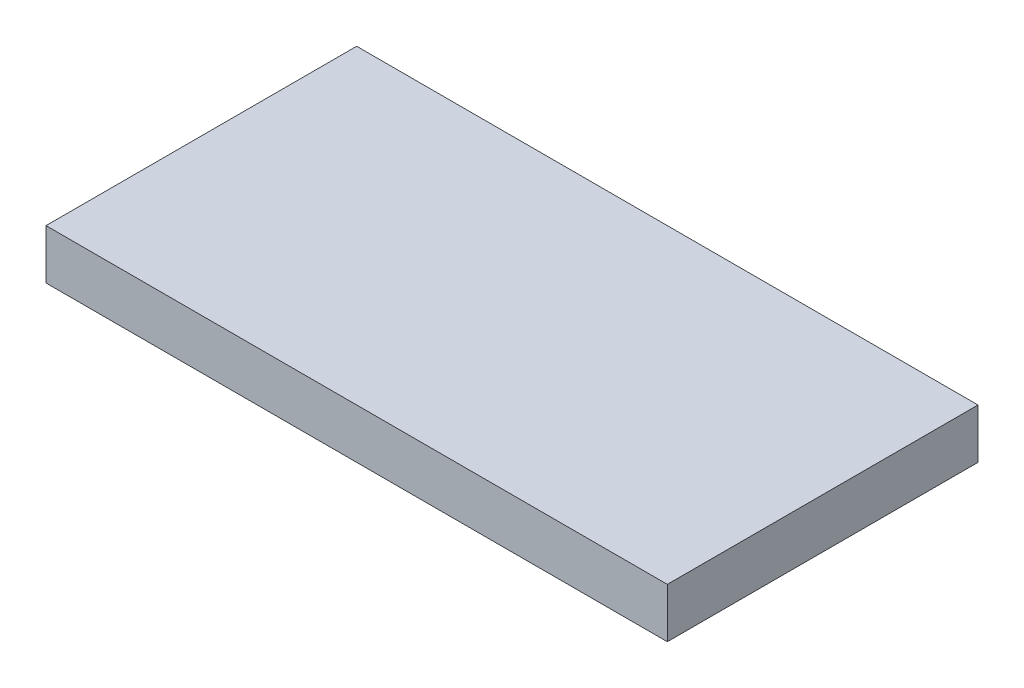
SolidWorks part; units mm, degrees
ref_plane "Front Plane" through (0, 0, 0) normal (0, 0, 1) x (1, 0, 0)
ref_plane "Top Plane" through (0, 0, 0) normal (0, 1, 0) x (1, 0, 0)
ref_plane "Right Plane" through (0, 0, 0) normal (1, 0, 0) x (0, 0, -1)
sketch "Sketch1" plane through (0, 0, 0) normal (0, 1, 0) x (1, 0, 0)
  line L1 (0, 0) -> (20, 0)
  line L2 (0, 0) -> (0, 10)
  line L3 (0, 10) -> (20, 10)
  line L4 (20, 0) -> (20, 10)
  dimension "D1" = 10
  dimension "D2" = 20
extrude "Boss-Extrude1" add sketch "Sketch1" along normal blind 1.6 contours L3 L4 L1 L2
